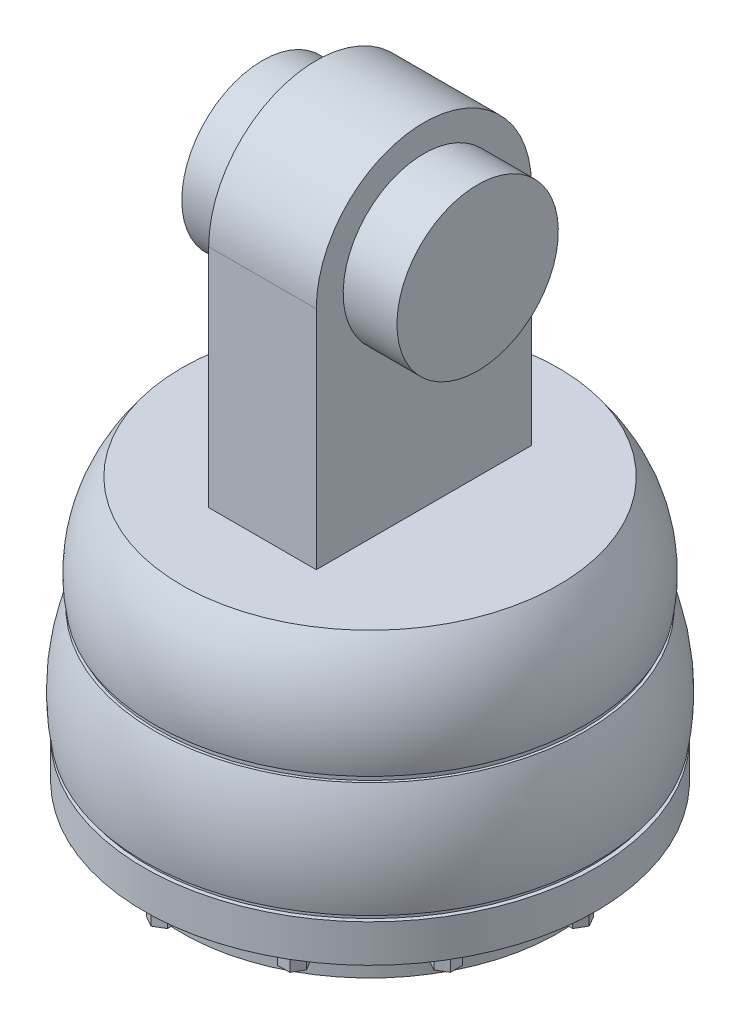
SolidWorks part; units mm, degrees
ref_plane "Front Plane" through (0, 0, 0) normal (0, 0, 1) x (1, 0, 0)
ref_plane "Top Plane" through (0, 0, 0) normal (0, 1, 0) x (1, 0, 0)
ref_plane "Right Plane" through (0, 0, 0) normal (1, 0, 0) x (0, 0, -1)
sketch "Sketch1" plane through (0, 0, 0) normal (0, 0, 1) x (1, 0, 0)
  line L0 (-35, 0) -> (0, 0)
  line L1 (0, 0) -> (0, -20)
  line L2 (0, -20) -> (-40, -20)
  arc A0 (-35, 0) -> (-40, -20) centre (-15.404, -15.524) ccw
  dimension "D4" = 25
  dimension "D1" = 35
  dimension "D2" = 20
  dimension "D3" = 40
revolve "Revolve1" add sketch "Sketch1" angle 360 about L1
sketch "Sketch2" plane through (0, -20, 0) normal (0, -1, 0) x (1, 0, 0)
  circle A0 centre (0, 0) radius 39.5
  dimension "D1" = 79
extrude "Boss-Extrude1" add sketch "Sketch2" along normal blind 1
sketch "Sketch3" plane through (0, 0, 0) normal (1, 0, 0) x (0, 0, -1)
  line L0 (0, -21) -> (-40, -21)
  line L1 (-39.5, -21) -> (39.5, -21) construction
  line L2 (0, -21) -> (0, -41)
  line L3 (0, -41) -> (-42, -41)
  arc A0 (-40, -21) -> (-42, -41) centre (-5.5677, -34.5432) ccw
  dimension "D4" = 37
  dimension "D1" = 40
  dimension "D2" = 20
  dimension "D3" = 42
revolve "Revolve2" add sketch "Sketch3" angle 360 about L2
sketch "Sketch4" plane through (0, -41, 0) normal (0, -1, 0) x (1, 0, 0)
  circle A0 centre (0, 0) radius 41.25
  dimension "D1" = 82.5
extrude "Boss-Extrude2" add sketch "Sketch4" along normal blind 1
sketch "Sketch5" plane through (0, -42, 0) normal (0, -1, 0) x (1, 0, 0)
  circle A0 centre (0, 0) radius 42
  dimension "D1" = 84
extrude "Boss-Extrude3" add sketch "Sketch5" along normal blind 7
sketch "Sketch6" plane through (0, -49, 0) normal (0, -1, 0) x (1, 0, 0)
  circle A0 centre (0, 0) radius 35
  dimension "D1" = 70
extrude "Boss-Extrude4" add sketch "Sketch6" along normal blind 7
sketch "Sketch7" plane through (0, -49, 0) normal (0, -1, 0) x (1, 0, 0)
  line L0 (35, 0) -> (42, 0) construction
  line L1 (39.0476, 0.9486) -> (37.9524, 0.9486)
  line L2 (40.75, 0) -> (39.625, 1.9486)
  line L3 (39.625, 1.9486) -> (37.375, 1.9486)
  line L4 (37.375, 1.9486) -> (36.25, 0)
  line L5 (36.25, 0) -> (37.375, -1.9486)
  line L6 (37.375, -1.9486) -> (39.625, -1.9486)
  line L7 (39.625, -1.9486) -> (40.75, 0)
  line L8 (37.9524, 0.9486) -> (37.4047, 0)
  line L9 (37.4047, 0) -> (37.9524, -0.9486)
  line L10 (37.9524, -0.9486) -> (39.0476, -0.9486)
  line L11 (39.0476, -0.9486) -> (39.5953, 0)
  line L12 (39.5953, 0) -> (39.0476, 0.9486)
  circle A0 centre (0, 0) radius 35 construction
  circle A1 centre (0, 0) radius 35 construction
  circle A2 centre (0, 0) radius 42 construction
  circle A3 centre (38.5, 0) radius 1.9486 construction
  dimension "D1" = 4.5
  dimension "D2" = 1
extrude "Boss-Extrude5" add sketch "Sketch7" along normal blind 3
pattern_circular "CirPattern1" count 12 over 360 about axis through (0, 0, 0) along (0, 1, 0) of "Boss-Extrude5"
sketch "Sketch8" plane through (0, -56, 0) normal (0, -1, 0) x (1, 0, 0)
  circle A0 centre (0, 0) radius 15
  dimension "D1" = 30
extrude "Boss-Extrude6" add sketch "Sketch8" along normal blind 10
sketch "Sketch9" plane through (0, 0, 0) normal (0, 1, 0) x (1, 0, 0)
  line L1 (-10, -20) -> (10, -20)
  line L2 (-10, -20) -> (-10, 20)
  line L3 (-10, 20) -> (10, 20)
  line L4 (10, -20) -> (10, 20)
  line L5 (-10, -20) -> (10, 20) construction
  line L6 (-10, 20) -> (10, -20) construction
  point P0 (0, 0)
  dimension "D1" = 20
  dimension "D2" = 40
extrude "Boss-Extrude7" add sketch "Sketch9" along normal blind 42
sketch "Sketch10" plane through (-10, 0, 0) normal (-1, 0, 0) x (0, 0, 1)
  line L0 (-20, 42) -> (20, 42) construction
  line L1 (-20, 42) -> (20, 42)
  arc A0 (20, 42) -> (-20, 42) centre (0, 42) ccw
extrude "Boss-Extrude8" add sketch "Sketch10" against normal blind 20
sketch "Sketch11" plane through (-10, 0, 0) normal (-1, 0, 0) x (0, 0, 1)
  circle A0 centre (0, 42) radius 15
  dimension "D1" = 30
extrude "Boss-Extrude9" add sketch "Sketch11" along normal blind 10
mirror "Mirror1" about plane through (0, 0, 0) normal (1, 0, 0) of "Boss-Extrude9"
